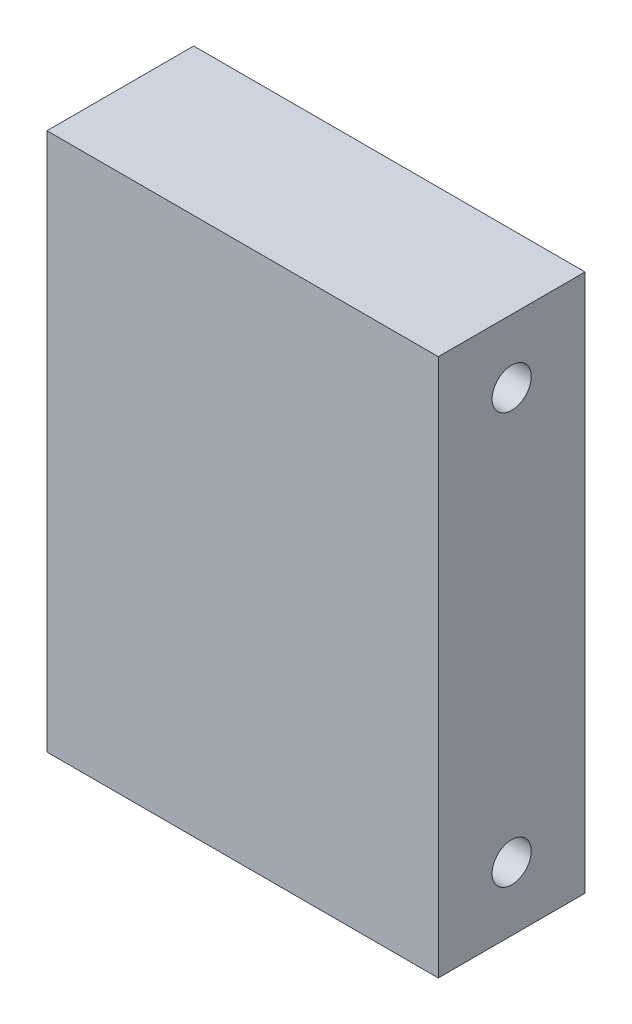
SolidWorks part; units mm, degrees
ref_plane "Plan de face" through (0, 0, 0) normal (0, 0, 1) x (1, 0, 0)
ref_plane "Plan de dessus" through (0, 0, 0) normal (0, 1, 0) x (1, 0, 0)
ref_plane "Plan de droite" through (0, 0, 0) normal (1, 0, 0) x (0, 0, -1)
sketch "Esquisse1" plane through (0, 0, 0) normal (0, 0, 1) x (1, 0, 0)
  line L1 (-20, 27.5) -> (20, 27.5)
  line L2 (-20, 27.5) -> (-20, -27.5)
  line L3 (-20, -27.5) -> (20, -27.5)
  line L4 (20, 27.5) -> (20, -27.5)
  dimension "D1" = 55
  dimension "D2" = 40
  dimension "D3" = 20
  dimension "D4" = 27.5
extrude "Boss.-Extru.1" add sketch "Esquisse1" along normal blind 15
sketch "Esquisse2" plane through (20, 0, 0) normal (1, 0, 0) x (0, 0, -1)
  line L0 (-15, -27.5) -> (0, -27.5) construction
  line L3 (-7.5, 21) -> (-7.5, -21) construction
  line L4 (-15, -27.5) -> (-15, 27.5) construction
  circle A0 centre (-7.5, 21) radius 2
  circle A1 centre (-7.5, -21) radius 2
  dimension "D1" = 4
  dimension "D2" = 4
  dimension "D4" = 6.5
  dimension "D3" = 42
  dimension "D5" = 7.5
extrude "Enlèv. mat.-Extru.1" cut sketch "Esquisse2" against normal blind 5
sketch "Esquisse3" plane through (-20, 0, 0) normal (-1, 0, 0) x (0, 0, 1)
  line L0 (15, -27.5) -> (0, -27.5) construction
  line L2 (7.5, 21) -> (7.5, -21) construction
  line L3 (0, 27.5) -> (0, -27.5) construction
  circle A0 centre (7.5, 21) radius 2
  circle A1 centre (7.5, -21) radius 2
  point P4 (7.5, -27.5)
  dimension "D1" = 4
  dimension "D2" = 4
  dimension "D4" = 6.5
  dimension "D3" = 42
  dimension "D5" = 7.5
extrude "Enlèv. mat.-Extru.2" cut sketch "Esquisse3" against normal blind 5
equation "\"D3@Esquisse1\"=\"D2@Esquisse1\"/2"
equation "\"D4@Esquisse1\"=\"D1@Esquisse1\"/2"
